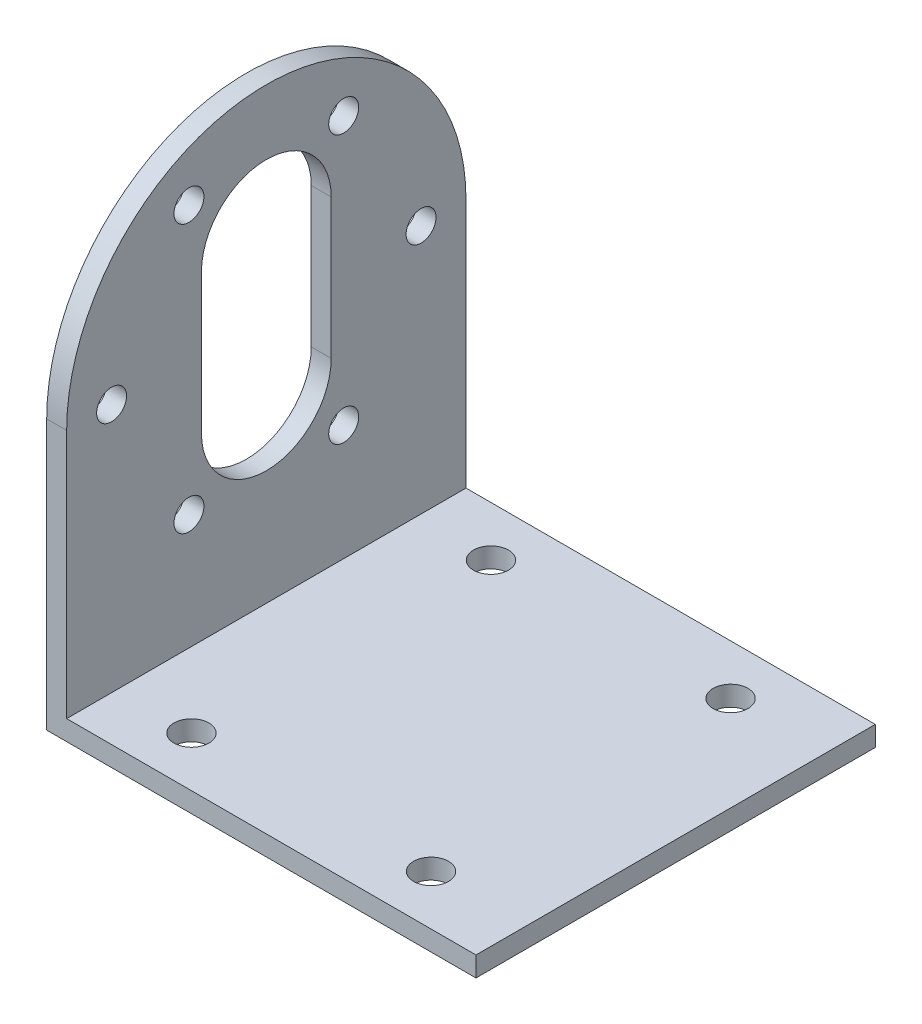
SolidWorks part; units mm, degrees
ref_plane "前视基准面" through (0, 0, 0) normal (0, 0, 1) x (1, 0, 0)
ref_plane "上视基准面" through (0, 0, 0) normal (0, 1, 0) x (1, 0, 0)
ref_plane "右视基准面" through (0, 0, 0) normal (1, 0, 0) x (0, 0, -1)
sketch "草图1" plane through (0, 0, 0) normal (1, 0, 0) x (0, 0, -1)
  line L0 (-20, 0) -> (-20, -27)
  line L1 (-20, -27) -> (20, -27)
  line L2 (20, -27) -> (20, 0)
  line L3 (0, 7) -> (0, -7) construction
  line L4 (6.5, 7) -> (6.5, -7)
  line L5 (-6.5, 7) -> (-6.5, -7)
  arc A0 (20, 0) -> (-20, 0) centre (0, 0) ccw
  circle A1 centre (0, 0) radius 15.5 construction
  circle A2 centre (-15.5, 0) radius 1.5
  arc A3 (6.5, 7) -> (-6.5, 7) centre (0, 7) ccw
  arc A4 (-6.5, -7) -> (6.5, -7) centre (0, -7) ccw
  circle A5 centre (-7.75, 13.4234) radius 1.5
  circle A6 centre (7.75, 13.4234) radius 1.5
  circle A7 centre (15.5, 0) radius 1.5
  circle A8 centre (7.75, -13.4234) radius 1.5
  circle A9 centre (-7.75, -13.4234) radius 1.5
  point P11 (0, 0)
  point P16 (0, 13.5)
  point P17 (0, -13.5)
  point P30 (0, 0)
  dimension "D1" = 40
  dimension "D3" = 31
  dimension "D4" = 3
  dimension "D5" = 6.5
  dimension "D2" = 27
  dimension "D6" = 27
  dimension "D7" = 6
extrude "凸台-拉伸1" add sketch "草图1" along normal blind 2 contours L0 L1 L2 A0
sketch "草图3" plane through (0, -27, 0) normal (0, -1, 0) x (1, 0, 0)
  line L1 (0, 20) -> (43, 20)
  line L2 (0, 20) -> (0, -20)
  line L3 (0, -20) -> (43, -20)
  line L4 (43, 20) -> (43, -20)
  circle A0 centre (9.5, 15) radius 1.75
  circle A1 centre (9.5, -15) radius 1.75
  circle A2 centre (33.5, 15) radius 1.75
  circle A3 centre (33.5, -15) radius 1.75
  point P13 (0, 0)
  point P14 (0, 0)
  point P15 (0, 0)
  point P16 (0, 0)
  dimension "D2" = 3.5
  dimension "D1" = 43
  dimension "D3" = 24
  dimension "D4" = 9.5
  dimension "D5" = 5
  dimension "30" = 30
extrude "凸台-拉伸2" add sketch "草图3" against normal blind 2
